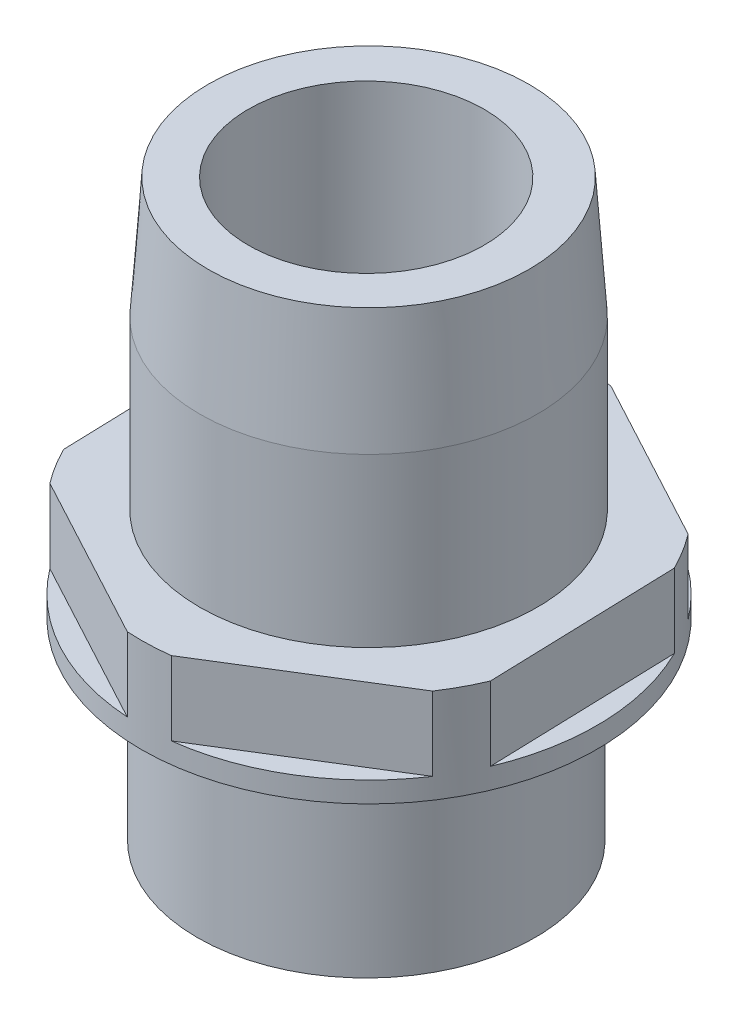
SolidWorks part; units mm, degrees
ref_plane "Front Plane" through (0, 0, 0) normal (0, 0, 1) x (1, 0, 0)
ref_plane "Top Plane" through (0, 0, 0) normal (0, 1, 0) x (1, 0, 0)
ref_plane "Right Plane" through (0, 0, 0) normal (1, 0, 0) x (0, 0, -1)
sketch "Sketch1" plane through (0, 0, 0) normal (0, 1, 0) x (1, 0, 0)
  circle A0 centre (-14.3288, 9.1626) radius 18.161
  dimension "D1" = 36.322
extrude "Boss-Extrude1" add sketch "Sketch1" along normal blind 1.651
sketch "Sketch2" plane through (0, 1.651, 0) normal (0, 1, 0) x (1, 0, 0)
  line L1 (2.4668, 0.1433) -> (1.8799, 19.1983)
  line L2 (1.8799, 19.1983) -> (-14.9157, 28.2176)
  line L3 (-14.9157, 28.2176) -> (-31.1245, 18.1818)
  line L4 (-31.1245, 18.1818) -> (-30.5376, -0.8732)
  line L5 (-30.5376, -0.8732) -> (-13.742, -9.8925)
  line L6 (-13.742, -9.8925) -> (2.4668, 0.1433)
  circle A0 centre (-14.3288, 9.1626) radius 16.51 construction
  dimension "D1" = 33.02
extrude "Boss-Extrude2" add sketch "Sketch2" along normal blind 5.8928
sketch "Sketch3" plane through (0, 7.5438, 0) normal (0, 1, 0) x (1, 0, 0)
  line L0 (-31.1245, 18.1818) -> (-30.3288, 17.7546) construction
  line L1 (-13.1835, 27.2874) -> (-14.9157, 28.2176)
  line L2 (1.8799, 19.1983) -> (0.1476, 20.1286)
  line L3 (-14.9157, 28.2176) -> (-16.5875, 27.1826)
  line L4 (-31.1245, 18.1818) -> (-31.0639, 16.2165)
  line L5 (-30.5376, -0.8732) -> (-28.8053, -1.8035)
  line L6 (-13.742, -9.8925) -> (-12.0702, -8.8575)
  line L7 (2.4668, 0.1433) -> (2.4062, 2.1086)
  line L8 (-29.4527, 19.2169) -> (-31.1245, 18.1818)
  line L9 (-28.8743, 16.9735) -> (0.2166, 1.3516) construction
  line L10 (-30.5981, 1.092) -> (-30.5376, -0.8732)
  line L11 (-15.4742, -8.9623) -> (-13.742, -9.8925)
  line L12 (0.7951, -0.8918) -> (2.4668, 0.1433)
  line L13 (1.6711, 0.5705) -> (2.4668, 0.1433) construction
  line L14 (1.9404, 17.2331) -> (1.8799, 19.1983)
  arc A0 (-29.4527, 19.2169) -> (-31.0639, 16.2165) centre (-14.3288, 9.1626) ccw
  arc A2 (-13.1835, 27.2874) -> (-16.5875, 27.1826) centre (-14.3288, 9.1626) ccw
  arc A3 (-30.5981, 1.092) -> (-28.8053, -1.8035) centre (-14.3288, 9.1626) ccw
  arc A4 (-15.4742, -8.9623) -> (-12.0702, -8.8575) centre (-14.3288, 9.1626) ccw
  arc A5 (0.7951, -0.8918) -> (2.4062, 2.1086) centre (-14.3288, 9.1626) ccw
  arc A6 (1.9404, 17.2331) -> (0.1476, 20.1286) centre (-14.3288, 9.1626) ccw
extrude "Cut-Extrude1" cut sketch "Sketch3" against normal up to next
sketch "Sketch5" plane through (0, 7.5438, 0) normal (0, 1, 0) x (1, 0, 0)
  line L0 (-23.0201, 23.1997) -> (-5.6376, -4.8746) construction
  line L1 (-16.5875, 27.1826) -> (-29.4527, 19.2169) construction
  line L2 (-12.0702, -8.8575) -> (0.7951, -0.8918) construction
  circle A0 centre (-14.2739, 9.0738) radius 13.462
  dimension "D1" = 26.924
extrude "Boss-Extrude3" add sketch "Sketch5" along normal blind 13.335
sketch "Sketch6" plane through (0, 20.8788, 0) normal (0, 1, 0) x (1, 0, 0)
  circle A0 centre (-14.2739, 9.0738) radius 13.462
  dimension "D1" = 26.924
extrude "Boss-Extrude4" add sketch "Sketch6" along normal blind 9.652 draft 4
sketch "Sketch7" plane through (0, 0, 0) normal (0, -1, 0) x (1, 0, 0)
  circle A0 centre (-14.3394, -8.9507) radius 13.462
  dimension "D1" = 26.924
extrude "Boss-Extrude5" add sketch "Sketch7" along normal blind 15.24
sketch "Sketch8" plane through (0, -15.24, 0) normal (0, -1, 0) x (1, 0, 0)
  circle A0 centre (-14.3394, -8.9507) radius 9.398
  dimension "D1" = 18.796
extrude "Cut-Extrude3" cut sketch "Sketch8" against normal through all
